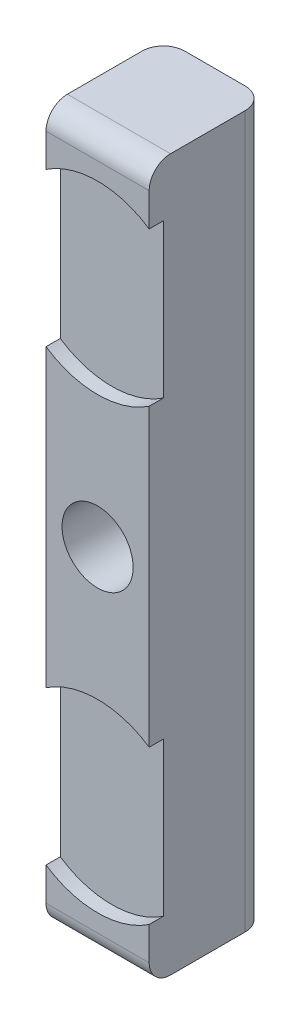
SolidWorks part; units mm, degrees
ref_plane "Front Plane" through (0, 0, 0) normal (1, 0, 0) x (0, 1, 0)
ref_plane "Top Plane" through (0, 0, 0) normal (0, 0, 1) x (0, 1, 0)
ref_plane "Right Plane" through (0, 0, 0) normal (0, 1, 0) x (-1, 0, 0)
sketch "Sketch7" plane through (0, 0, 0) normal (0, 0, 1) x (0, 1, 0)
  line L1 (-50, -7.25) -> (50, -7.25)
  line L2 (-50, -7.25) -> (-50, 7.25)
  line L3 (-50, 7.25) -> (50, 7.25)
  line L4 (50, -7.25) -> (50, 7.25)
  line L5 (-50, -7.25) -> (50, 7.25) construction
  line L6 (-50, 7.25) -> (50, -7.25) construction
  point P0 (0, 0)
  dimension "D1" = 14.5
  dimension "D2" = 100
extrude "Boss-Extrude1" add sketch "Sketch7" along normal blind 16.5
sketch "Sketch8" plane through (0, 0, 16.5) normal (0, 0, 1) x (0, -1, 0)
  circle A0 centre (0, 0) radius 5
  dimension "D1" = 10
extrude "Cut-Extrude2" cut sketch "Sketch8" against normal blind 13
sketch "Sketch10" plane through (0, 0, 16.5) normal (0, 0, 1) x (1, 0, 0)
  line L0 (0, 0) -> (0, -31.55) construction
  line L1 (-7.25, 0) -> (7.25, 0) construction
  line L2 (-7.25, 50) -> (-7.25, -50) construction
  line L3 (7.25, -50) -> (7.25, 50) construction
  circle A0 centre (0, -31.55) radius 13
  dimension "D2" = 26
  dimension "D1" = 31.55
extrude "Cut-Extrude3" cut sketch "Sketch10" against normal blind 2
mirror "Mirror1" about plane through (0, 0, 0) normal (0, 1, 0) of "Cut-Extrude3"
fillet "Fillet1" radius 3 1 edges at (-7.25, 0, 0)
fillet "Fillet3" radius 3 1 edges at (7.25, 0, 0)
fillet "Fillet4" radius 3 1 edges at (0, 50, 16.5)
fillet "Fillet5" radius 3 1 edges at (0, -50, 16.5)
